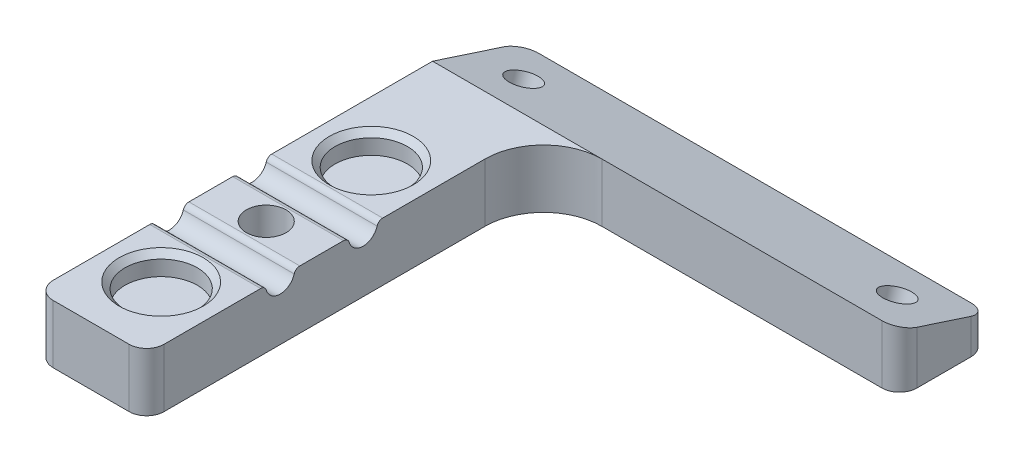
SolidWorks part; units mm, degrees
ref_plane "Front Plane" through (0, 0, 0) normal (0, 0, 1) x (1, 0, 0)
ref_plane "Top Plane" through (0, 0, 0) normal (0, 1, 0) x (1, 0, 0)
ref_plane "Right Plane" through (0, 0, 0) normal (1, 0, 0) x (0, 0, -1)
sketch "Sketch1" plane through (0, 0, 0) normal (0, 1, 0) x (1, 0, 0)
  line L1 (-4.75, -15) -> (4.75, -15)
  line L2 (-4.75, -15) -> (-4.75, 15)
  line L3 (-4.75, 15) -> (4.75, 15)
  line L4 (4.75, -15) -> (4.75, 15)
  line L5 (-4.75, -15) -> (4.75, 15) construction
  line L6 (-4.75, 15) -> (4.75, -15) construction
  point P0 (0, 0)
  dimension "D1" = 9.5
  dimension "D2" = 30
extrude "Boss-Extrude1" add sketch "Sketch1" along normal blind 5
sketch "Sketch2" plane through (0, 5, 0) normal (0, 1, 0) x (1, 0, 0)
  line L0 (0, 9) -> (0, -9) construction
  line L1 (4.75, 15) -> (-4.75, 15) construction
  circle A0 centre (0, 9) radius 3.1
  circle A1 centre (0, 0) radius 1.7
  circle A2 centre (0, -9) radius 3.1
  dimension "D1" = 6.2
  dimension "D2" = 3.4
  dimension "D3" = 6
extrude "Cut-Extrude1" cut sketch "Sketch2" against normal through all
sketch "Sketch8" plane through (0, 0, 0) normal (0, -1, 0) x (1, 0, 0)
  circle A0 centre (0, 9) radius 3.1
  circle A1 centre (0, -9) radius 3.1
  circle A2 centre (0, -9) radius 3.1 construction
  circle A3 centre (0, 9) radius 3.1 construction
extrude "Boss-Extrude3" add sketch "Sketch8" against normal offset from surface (3.2 mm away) 1.8 up to face at (0, 5, 12.1)
chamfer "Chamfer1" distance 0.5 angle 45 2 edges at (0, 5, 12.1) (0, 5, -5.9)
sketch "Sketch3" plane through (0, 5, 0) normal (0, 1, 0) x (1, 0, 0)
  line L0 (-4.75, 15) -> (-4.75, 19)
  line L1 (-4.75, 29) -> (35.25, 29)
  line L2 (-4.75, 29) -> (-4.75, 19)
  line L3 (4.75, 19) -> (35.25, 19)
  line L4 (35.25, 29) -> (35.25, 19)
  line L5 (-4.75, 29) -> (35.25, 19) construction
  line L6 (-4.75, 19) -> (35.25, 29) construction
  line L7 (4.75, 15) -> (4.75, 19)
  line L8 (4.75, -15) -> (4.75, 15) construction
  line L9 (-4.75, 15) -> (-4.75, -15) construction
  line L10 (4.75, 15) -> (-4.75, 15)
  point P0 (15.25, 24)
  dimension "D1" = 40
  dimension "D2" = 4
  dimension "D3" = 10
extrude "Boss-Extrude2" add sketch "Sketch3" against normal up to surface (5 mm away) up to face at (0, 0, 1.7)
sketch "Sketch5" plane through (35.25, 0, 0) normal (1, 0, 0) x (0, 0, -1)
  line L0 (19, 5) -> (29, 1.7508)
  line L1 (29, 0) -> (29, 5) construction
  line L2 (29, 1.7508) -> (29, 5)
  line L3 (29, 5) -> (19, 5)
  dimension "D1" = 18
extrude "Cut-Extrude2" cut sketch "Sketch5" against normal through all
sketch "Sketch6" plane through (0, 10.1065, -3.2838) normal (0, 0.9511, -0.309) x (1, 0, 0)
  line L0 (31.25, 20.525) -> (-0.75, 20.525) construction
  line L1 (-0.75, 20.525) -> (-4.75, 20.525) construction
  line L2 (-4.75, 16.525) -> (-4.75, 27.0396) construction
  line L3 (31.25, 20.525) -> (35.25, 20.525) construction
  line L5 (35.25, 16.525) -> (35.25, 27.0396) construction
  line L6 (-4.75, 16.525) -> (4.75, 16.525) construction
  circle A0 centre (-0.75, 20.525) radius 1.3
  circle A1 centre (31.25, 20.525) radius 1.3
  dimension "D1" = 2.6
  dimension "D2" = 32
  dimension "D3" = 4
extrude "Cut-Extrude3" cut sketch "Sketch6" against normal through all
sketch "Sketch9" plane through (35.25, 0, 0) normal (1, 0, 0) x (0, 0, -1)
  line L1 (29, 0) -> (26.6085, 0)
  line L2 (29, 0) -> (29, 2.5279)
  line L3 (29, 2.5279) -> (26.6085, 2.5279)
  line L4 (26.6085, 0) -> (26.6085, 2.5279)
  line L5 (29, 0) -> (26.6085, 2.5279) construction
  line L6 (29, 2.5279) -> (26.6085, 0) construction
  line L7 (19, 5) -> (29, 1.7508) construction
  point P0 (27.8042, 1.2639)
  dimension "D1" = 2.7
extrude "Cut-Extrude4" cut sketch "Sketch9" against normal through all
fillet "Fillet2" radius 1.5 5 edges at (35.25, 2.5, -19) (-4.75, 2.5, 15) (4.75, 2.5, 15) (-4.75, 1.2639, -26.6085) (35.25, 1.2639, -26.6085)
fillet "Fillet1" radius 5 1 edges at (4.75, 2.5, -19)
sketch "Sketch10" plane through (0, 0, 0) normal (0, -1, 0) x (1, 0, 0)
  circle A0 centre (0, 0) radius 3.25
  dimension "D1" = 6.5
extrude "Cut-Extrude5" cut sketch "Sketch10" against normal blind 2
sketch "Sketch13" plane through (-4.75, 0, 0) normal (-1, 0, 0) x (0, 0, 1)
  line L0 (-19, 5) -> (13.5, 5) construction
  line L2 (0, -2.75) -> (0, 2.75) construction
  line L3 (-3.55, 5) -> (3.55, 5) construction
  circle A0 centre (-3.55, 5) radius 1.25
  circle A1 centre (3.55, 5) radius 1.25
  point P8 (0, 5)
  dimension "D2" = 2.5
  dimension "D1" = 3.55
extrude "Cut-Extrude6" cut sketch "Sketch13" against normal through all
fillet "Fillet3" radius 0.5 4 edges at (0, 5, 2.3) (0, 5, 4.8) (0, 5, -4.8) (0, 5, -2.3)
equation "\"M3_d\"= 3.4"
equation "\"M3_tap_d\"=2.6"
equation "\"D2@Sketch2\"=\"M3_d\""
equation "\"D1@Sketch6\"=\"M3_tap_d\""
